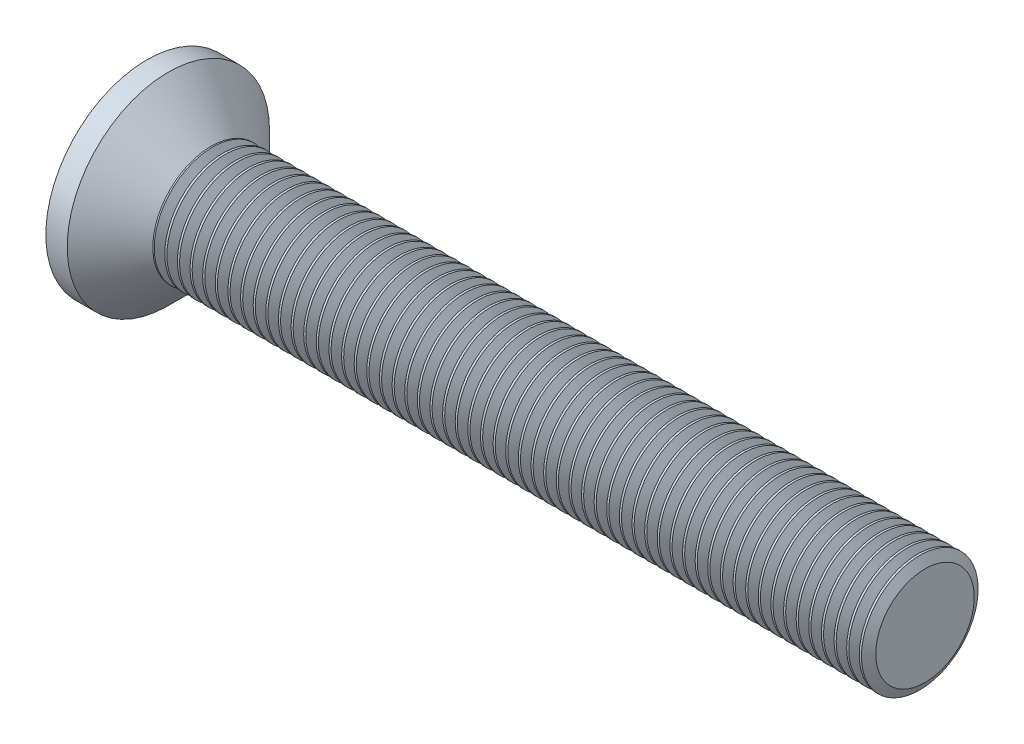
SolidWorks part; units mm, degrees
ref_plane "Front" through (0, 0, 0) normal (0, 0, 1) x (1, 0, 0)
ref_plane "Top" through (0, 0, 0) normal (0, 1, 0) x (1, 0, 0)
ref_plane "Right" through (0, 0, 0) normal (1, 0, 0) x (0, 0, -1)
sketch "Sketch1" plane through (0, 0, 0) normal (0, 0, 1) x (1, 0, 0)
  line L0 (20, 1.5) -> (2.65, 1.5)
  line L1 (2.65, 1.5) -> (1.65, 1.5)
  line L2 (1.65, 1.5) -> (0.55, 2.6)
  line L3 (0.55, 2.6) -> (0, 2.6)
  line L4 (20, 1.5) -> (20, 0)
  line L5 (4.5158, 0) -> (-89.8219, 0) construction
  line L6 (20, 0) -> (0, 0)
  line L7 (0, 2.6) -> (0, 0)
  dimension "D1" = 45
  dimension "dk" = 5.2
  dimension "l" = 20
  dimension "k" = 1.65
  dimension "a" = 1
  dimension "d" = 3
revolve "Base" add sketch "Sketch1" angle 360 about L5
cosmetic thread "ThreadCosmetic1" [suppressed] parameters "bb"=18.35
sketch "Sketch6" plane through (0, 0, 0) normal (1, 0, 0) x (0, 0, -1)
  line L0 (-1.9271, 0) -> (2.0512, 0) construction
  line L1 (0, 1.8651) -> (0, -2.0207) construction
  line L2 (0.32, 0.32) -> (0.32, 1.6)
  line L3 (0.32, 1.6) -> (-0.32, 1.6)
  line L4 (-0.32, 0.32) -> (-0.32, 1.6)
  line L5 (0.32, 0.32) -> (1.6, 0.32)
  line L6 (1.6, 0.32) -> (1.6, -0.32)
  line L7 (-1.6, 0.32) -> (-1.6, -0.32)
  line L8 (-0.32, 0.32) -> (-1.6, 0.32)
  line L9 (-0.32, -0.32) -> (-1.6, -0.32)
  line L10 (0.32, -0.32) -> (1.6, -0.32)
  line L11 (-0.32, -0.32) -> (-0.32, -1.6)
  line L12 (0.32, -1.6) -> (-0.32, -1.6)
  line L13 (0.32, -0.32) -> (0.32, -1.6)
  point P16 (-1.6, 0)
  point P17 (1.6, 0)
extrude "CrossRecess" cut sketch "Sketch6" along normal blind 0.825
draft "Draft9" type of draft neutral plane draft angle 30 faces to draft 4 face at (0.4125, -1.6, 0) face at (0.4125, 0, 1.6) face at (0.4125, 0, -1.6) face at (0.4125, 1.6, 0) neutral plane through (0, 2.6, 0) neutral plane normal (-1, 0, 0) parameters "D1"=30
fillet "Fillet5" radius 0.3 4 edges at (0.4125, -0.32, -0.32) (0.4125, -0.32, 0.32) (0.4125, 0.32, -0.32) (0.4125, 0.32, 0.32)
sketch "Sketch7" plane through (0, 0, 0) normal (1, 0, 0) x (0, 0, -1)
  line L0 (-2.0126, 0) -> (1.9757, 0) construction
  line L1 (0, 1.9314) -> (0, -2.0126) construction
  line L2 (0, 0) -> (1.5555, 1.5555) construction
  line L3 (0, 0.4782) -> (1.1314, 1.1314)
  line L4 (-1.5402, 1.5402) -> (0, 0) construction
  line L5 (0.4782, 0) -> (1.1314, 1.1314)
  line L6 (0, -0.4782) -> (1.1314, -1.1314)
  line L7 (0.4782, 0) -> (1.1314, -1.1314)
  line L8 (-0.4782, 0) -> (-1.1314, -1.1314)
  line L9 (0, -0.4782) -> (-1.1314, -1.1314)
  line L10 (-0.4782, 0) -> (-1.1314, 1.1314)
  line L11 (0, 0.4782) -> (-1.1314, 1.1314)
  dimension "D3" = 15
  dimension "m" = 3.2
extrude "Cut-Extrude3" [suppressed] cut sketch "Sketch7" along normal blind 10 draft 20
sketch "Sketch10" plane through (0, 0, 0) normal (0, 0, 1) x (1, 0, 0)
  line L0 (62.2289, 0) -> (-1.9277, 0) construction
  line L1 (1.65, 1.5) -> (2.15, 1.5)
  line L4 (2.15, 1.5) -> (2.15, 0)
  line L7 (2.15, 0) -> (1.65, 0)
  line L9 (1.65, 1.5) -> (0.55, 2.6) construction
  line L10 (1.65, 1.5) -> (1.65, 0)
  dimension "p" = 0.5
revolve "Revolve2" add sketch "Sketch10" angle 360 about L0
sketch "Sketch8" plane through (0, 0, 0) normal (0, 0, 1) x (1, 0, 0)
  line L0 (-5, 1.5) -> (-6.25, 1.2295)
  line L1 (-6.25, 1.2295) -> (5, 1.2295)
  line L3 (20, -1.5) -> (20, 1.5) construction
  line L6 (5, 1.2295) -> (5, 6.2295)
  line L7 (5, 6.2295) -> (-5, 6.2295)
  line L8 (-5, 6.2295) -> (-5, 1.5)
  line L9 (62.4753, 0) -> (52.9594, 0) construction
  dimension "D1" = 5
  dimension "x" = 1.25
  dimension "d" = 3
  dimension "THD_MINOR" = 2.459
  dimension "b" = 25
sketch "Sketch11" plane through (0, 0, 0) normal (0, 0, 1) x (1, 0, 0)
  line L0 (20, 1.2657) -> (20.1352, 1.5)
  line L1 (20.1352, 1.5) -> (20.1352, 1.7705)
  line L2 (20.1352, 1.7705) -> (19.8648, 1.7705)
  line L3 (19.8648, 1.7705) -> (19.8648, 1.5)
  line L4 (19.8648, 1.5) -> (20, 1.2657)
  line L5 (20, -1.5) -> (20, 1.5) construction
  line L6 (0, 0) -> (66.0064, 0) construction
  dimension "D1" = 3
  dimension "D2" = 0.2705
revolve "Cut-Revolve10" cut sketch "Sketch11" angle 360 about L6
pattern_linear "LPattern10" count 57 spacing 0.3246 along (-1, 0, 0) of "Cut-Revolve10"
equation "\"D1@Sketch6\" = \"m@Sketch6\" / 5"
equation "\"D1@CrossRecess\" = \"k@Sketch1\" / 2"
equation "\"D1@Sketch11\" = \"d@Sketch1\""
equation "\"D2@Sketch11\" =  ( \"d@Sketch1\" - \"THD_MINOR@ThreadCosmetic1\" )  / 2"
equation "\"D3@LPattern10\" = \"D2@Sketch11\" * 1.2"
equation "\"D1@LPattern10\" = \"bb@ThreadCosmetic1\" / \"D3@LPattern10\" "
